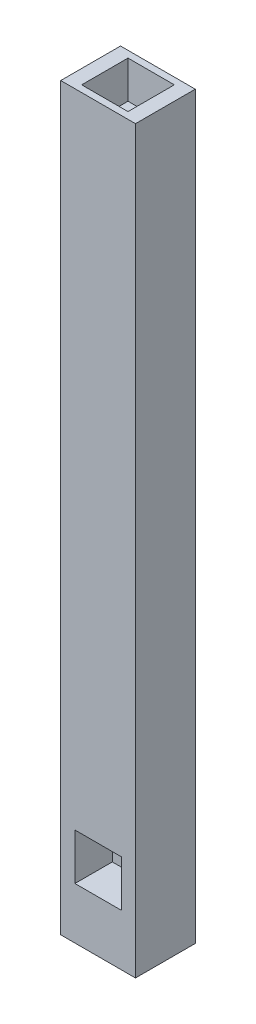
SolidWorks part; units mm, degrees
ref_plane "Front Plane" through (0, 0, 0) normal (0, 0, 1) x (1, 0, 0)
ref_plane "Top Plane" through (0, 0, 0) normal (0, 1, 0) x (1, 0, 0)
ref_plane "Right Plane" through (0, 0, 0) normal (1, 0, 0) x (0, 0, -1)
sketch "Sketch1" plane through (0, 0, 0) normal (0, 0, 1) x (1, 0, 0)
  line L0 (0, 12.7) -> (0, 127) construction
  line L2 (-6.35, 12.7) -> (6.35, 12.7)
  line L5 (-6.35, 12.7) -> (-6.35, 138.43)
  line L6 (-6.35, 138.43) -> (6.35, 138.43)
  line L7 (6.35, 12.7) -> (6.35, 138.43)
  point P15 (0, 0)
  dimension "D6" = 12.7
  dimension "D7" = 125.73
extrude "Boss-Extrude1" add sketch "Sketch1" along normal blind 10.16
sketch "Sketch4" plane through (0, 138.43, 0) normal (0, 1, 0) x (1, 0, 0)
  line L0 (6.35, -5.08) -> (0, -5.08) construction
  line L2 (-6.35, -10.16) -> (6.35, -10.16) construction
  line L5 (3.937, -9.017) -> (-3.937, -9.017)
  line L6 (3.937, -9.017) -> (3.937, -1.143)
  line L7 (3.937, -1.143) -> (-3.937, -1.143)
  line L8 (-3.937, -9.017) -> (-3.937, -1.143)
  line L9 (3.937, -9.017) -> (-3.937, -1.143) construction
  line L10 (3.937, -1.143) -> (-3.937, -9.017) construction
  line L11 (6.35, -10.16) -> (6.35, 0) construction
  dimension "D1" = 7.874
  dimension "D2" = 7.874
  dimension "D3" = 1.143
  dimension "D4" = 2.413
extrude "Cut-Extrude2" cut sketch "Sketch4" against normal blind 6.35
sketch "Sketch6" plane through (0, 0, 10.16) normal (0, 0, 1) x (1, 0, 0)
  line L0 (-6.35, 12.7) -> (-6.35, 138.43) construction
  line L1 (-3.937, 21.463) -> (3.937, 21.463)
  line L2 (-3.937, 21.463) -> (-3.937, 29.337)
  line L3 (-3.937, 29.337) -> (3.937, 29.337)
  line L4 (3.937, 21.463) -> (3.937, 29.337)
  line L5 (-3.937, 21.463) -> (3.937, 29.337) construction
  line L6 (-3.937, 29.337) -> (3.937, 21.463) construction
  line L7 (-6.35, 12.7) -> (6.35, 12.7) construction
  point P0 (0, 25.4)
  dimension "D1" = 7.874
  dimension "D2" = 7.874
  dimension "D3" = 2.413
  dimension "D4" = 8.763
extrude "Cut-Extrude4" cut sketch "Sketch6" against normal blind 6.35
sketch "Sketch8" plane through (0, 12.7, 0) normal (0, -1, 0) x (1, 0, 0)
  line L0 (-6.35, 0) -> (6.35, 0) construction
  line L1 (-3.937, 9.017) -> (3.937, 9.017)
  line L2 (-3.937, 9.017) -> (-3.937, 1.143)
  line L3 (-3.937, 1.143) -> (3.937, 1.143)
  line L4 (3.937, 9.017) -> (3.937, 1.143)
  line L5 (-3.937, 9.017) -> (3.937, 1.143) construction
  line L6 (-3.937, 1.143) -> (3.937, 9.017) construction
  line L7 (6.35, 10.16) -> (6.35, 0) construction
  point P0 (0, 5.08)
  dimension "D1" = 1.143
  dimension "D2" = 2.413
  dimension "D3" = 7.874
  dimension "D4" = 7.874
extrude "Cut-Extrude5" cut sketch "Sketch8" against normal blind 6.35
